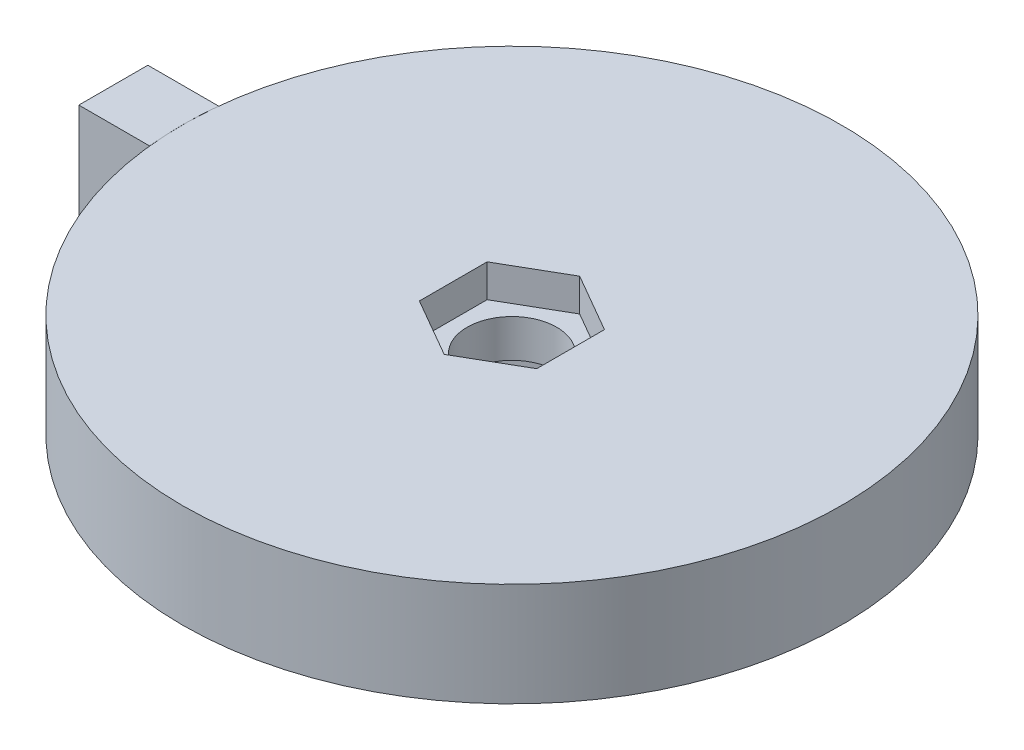
SolidWorks part; units mm, degrees
ref_plane "Plan de face" through (0, 0, 0) normal (0, 0, 1) x (1, 0, 0)
ref_plane "Plan de dessus" through (0, 0, 0) normal (0, 1, 0) x (1, 0, 0)
ref_plane "Plan de droite" through (0, 0, 0) normal (1, 0, 0) x (0, 0, -1)
sketch "Esquisse1" plane through (0, 0, 0) normal (0, 1, 0) x (1, 0, 0)
  circle A0 centre (0, 0) radius 47.75
  dimension "D1" = 95.5
extrude "Boss.-Extru.1" add sketch "Esquisse1" along normal blind 15
sketch "Esquisse2" plane through (0, 0, 0) normal (0, -1, 0) x (1, 0, 0)
  line L0 (-47.75, 0) -> (-57.75, 0)
  line L1 (-57.75, 0) -> (-57.75, -5)
  line L2 (-57.75, 0) -> (-57.75, 5)
  line L3 (-57.75, 5) -> (-47.4875, 5)
  line L4 (-57.75, -5) -> (-47.4875, -5)
  line L5 (-47.4875, -5) -> (-47.4875, 5)
  circle A0 centre (0, 0) radius 47.75 construction
  circle M4 centre (0, 0) radius 47.75
  dimension "D1" = 10
  dimension "D2" = 5
extrude "Boss.-Extru.2" add sketch "Esquisse2" against normal blind 15 separate body contours L1 L4 L0 M4 | L3 L2 L0 M4
sketch "Esquisse3" plane through (0, 15, 0) normal (0, 1, 0) x (1, 0, 0)
  circle A0 centre (0, 0) radius 6.5
  dimension "D1" = 13
extrude "Enlèv. mat.-Extru.1" cut sketch "Esquisse3" against normal through all contours A0
sketch "Esquisse4" plane through (0, 15, 0) normal (0, 1, 0) x (1, 0, 0)
  line L12 (-4, 6.9282) -> (-8, 4.6188)
  line L13 (-8, 4.6188) -> (-8, 0)
  line L14 (-8, 0) -> (-8, -4.6188)
  line L15 (-8, -4.6188) -> (-4, -6.9282)
  line L16 (-4, -6.9282) -> (0, -9.2376)
  line L17 (0, -9.2376) -> (4, -6.9282)
  line L18 (4, -6.9282) -> (8, -4.6188)
  line L19 (8, -4.6188) -> (8, 0)
  line L20 (8, 0) -> (8, 4.6188)
  line L21 (8, 4.6188) -> (4, 6.9282)
  line L22 (4, 6.9282) -> (0, 9.2376)
  line L23 (0, 9.2376) -> (-4, 6.9282)
  line L24 (4.25, 7.3612) -> (0, 9.815)
  line L25 (0, 9.815) -> (-4.25, 7.3612)
  line L26 (-4.25, 7.3612) -> (-8.5, 4.9075)
  line L27 (-8.5, 4.9075) -> (-8.5, 0)
  line L28 (-8.5, 0) -> (-8.5, -4.9075)
  line L29 (-8.5, -4.9075) -> (-4.25, -7.3612)
  line L30 (-4.25, -7.3612) -> (0, -9.815)
  line L31 (0, -9.815) -> (4.25, -7.3612)
  line L32 (4.25, -7.3612) -> (8.5, -4.9075)
  line L33 (8.5, -4.9075) -> (8.5, 0)
  line L34 (8.5, 0) -> (8.5, 4.9075)
  line L35 (8.5, 4.9075) -> (4.25, 7.3612)
  dimension "D1" = 0.5
extrude "Enlèv. mat.-Extru.3" cut sketch "Esquisse4" against normal blind 4.75 contours L35 L24 L25 L26 L27 L28 L29 L30 L31 L32 L33 L34
sketch "Esquisse5" plane through (0, 0, 0) normal (0, -1, 0) x (1, 0, 0)
  line L0 (-8.5, 4.9075) -> (0, 9.815) construction
  line L1 (0, 9.815) -> (8.5, 4.9075) construction
  line L2 (8.5, 4.9075) -> (8.5, -4.9075) construction
  line L3 (8.5, -4.9075) -> (0, -9.815) construction
  line L4 (0, -9.815) -> (-8.5, -4.9075) construction
  line L5 (-8.5, -4.9075) -> (-8.5, 4.9075) construction
  line L6 (-8.5, 4.9075) -> (0, 9.815)
  line L7 (0, 9.815) -> (8.5, 4.9075)
  line L8 (8.5, 4.9075) -> (8.5, -4.9075)
  line L9 (8.5, -4.9075) -> (0, -9.815)
  line L10 (0, -9.815) -> (-8.5, -4.9075)
  line L11 (-8.5, -4.9075) -> (-8.5, 4.9075)
extrude "Enlèv. mat.-Extru.4" cut sketch "Esquisse5" against normal blind 4.75 contours L11 L6 L7 L8 L9 L10
